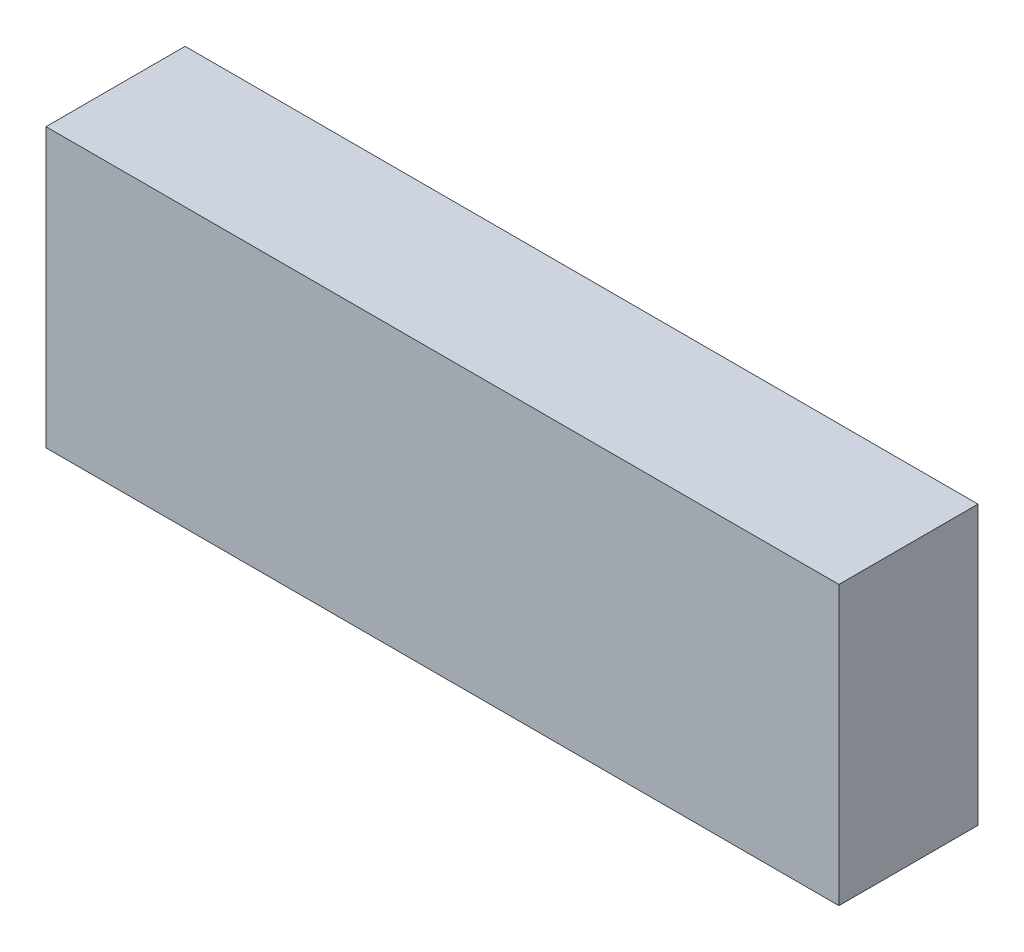
SolidWorks part; units mm, degrees
ref_plane "Front Plane" through (0, 0, 0) normal (0, 0, 1) x (1, 0, 0)
ref_plane "Top Plane" through (0, 0, 0) normal (0, 1, 0) x (1, 0, 0)
ref_plane "Right Plane" through (0, 0, 0) normal (1, 0, 0) x (0, 0, -1)
sketch "Sketch1" plane through (0, 0, 0) normal (0, 0, 1) x (1, 0, 0)
  line L1 (0, 0) -> (57, 0)
  line L2 (0, 0) -> (0, 20)
  line L3 (0, 20) -> (57, 20)
  line L4 (57, 0) -> (57, 20)
extrude "Boss-Extrude1" add sketch "Sketch1" against normal blind 10
